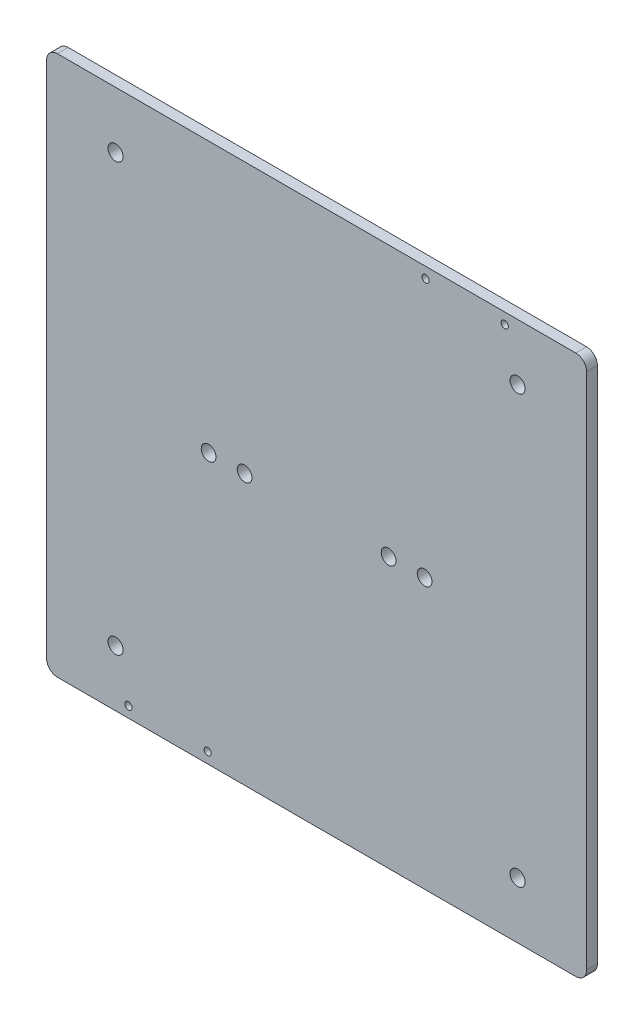
SolidWorks part; units mm, degrees
material "Thornel Mat VMA"
ref_plane "Front Plane" through (0, 0, 0) normal (0, 0, 1) x (1, 0, 0)
ref_plane "Top Plane" through (0, 0, 0) normal (0, 1, 0) x (1, 0, 0)
ref_plane "Right Plane" through (0, 0, 0) normal (1, 0, 0) x (0, 0, -1)
sketch "Sketch1" plane through (0, 0, 0) normal (0, 0, 1) x (1, 0, 0)
  line L1 (-75, -75) -> (75, -75)
  line L2 (-75, -75) -> (-75, 75)
  line L3 (-75, 75) -> (75, 75)
  line L4 (75, -75) -> (75, 75)
  line L5 (-75, -75) -> (75, 75) construction
  line L6 (-75, 75) -> (75, -75) construction
  point P0 (0, 0)
  dimension "D1" = 150
  dimension "D2" = 150
extrude "Boss-Extrude1" add sketch "Sketch1" along normal blind 3
fillet "Fillet1" radius 3 4 edges at (75, -75, 1.5) (-75, -75, 1.5) (-75, 75, 1.5) (75, 75, 1.5)
sketch "Sketch2" plane through (0, 0, 0) normal (0, 0, -1) x (-1, 0, 0)
  line L1 (-55.835, -59.325) -> (55.835, -59.325) construction
  line L2 (-55.835, -59.325) -> (-55.835, 59.325) construction
  line L3 (-55.835, 59.325) -> (55.835, 59.325) construction
  line L4 (55.835, -59.325) -> (55.835, 59.325) construction
  line L5 (-55.835, -59.325) -> (55.835, 59.325) construction
  line L6 (-55.835, 59.325) -> (55.835, -59.325) construction
  circle A0 centre (-55.835, 59.325) radius 2.1
  circle A1 centre (55.835, 59.325) radius 2.1
  circle A2 centre (-55.835, -59.325) radius 2.1
  circle A3 centre (55.835, -59.325) radius 2.1
  point P0 (0, 0)
  dimension "D1" = 118.65
  dimension "D2" = 111.67
extrude "Cut-Extrude1" cut sketch "Sketch2" against normal up to surface (3 mm away) up to face at (0, 0, 3)
sketch "Sketch3" plane through (0, 0, 0) normal (0, 0, -1) x (-1, 0, 0)
  line L0 (-75, 72) -> (75, 72) construction
  line L1 (-75, -72) -> (-75, 72) construction
  line L2 (75, 72) -> (75, -72) construction
  line L3 (-72, 75) -> (72, 75) construction
  line L4 (-75, -72) -> (75, -72) construction
  line L5 (72, -75) -> (-72, -75) construction
  circle A0 centre (-52.26, 72) radius 1
  circle A1 centre (-30.26, 72) radius 1
  circle A2 centre (52.26, -72) radius 1
  circle A3 centre (30.26, -72) radius 1
  dimension "D2" = 2
  dimension "D4" = 22
  dimension "D5" = 2
  dimension "D7" = 2
  dimension "D9" = 2
  dimension "D1" = 3
  dimension "D3" = 22.74
  dimension "D6" = 3
  dimension "D8" = 22.74
  dimension "D10" = 22
extrude "Cut-Extrude2" cut sketch "Sketch3" against normal up to surface (3 mm away) up to face at (-57.935, 59.325, 3)
sketch "草图2" plane through (0, 0, 3) normal (0, 0, 1) x (1, 0, 0)
  line L1 (0, 75) -> (0, -65) construction
  line L2 (72, 75) -> (-72, 75) construction
  line L3 (-75, 0) -> (75, 0) construction
  line L5 (75, -72) -> (75, 72) construction
  line L6 (-75, 72) -> (-75, -72) construction
  circle A0 centre (-30, 0) radius 2.05
  circle A1 centre (-20, 0) radius 2.05
  circle A4 centre (30, 0) radius 2.05
  circle A5 centre (20, 0) radius 2.05
  point P5 (20.5752, 0)
  point P6 (36.6695, 0)
  point P17 (-62.5, 0)
  point P22 (-52.1155, 0)
  point P23 (-42.4347, 0)
  dimension "D1" = 4.1
  dimension "D2" = 20
  dimension "D3" = 10
extrude "切除-拉伸1" cut sketch "草图2" against normal up to next
